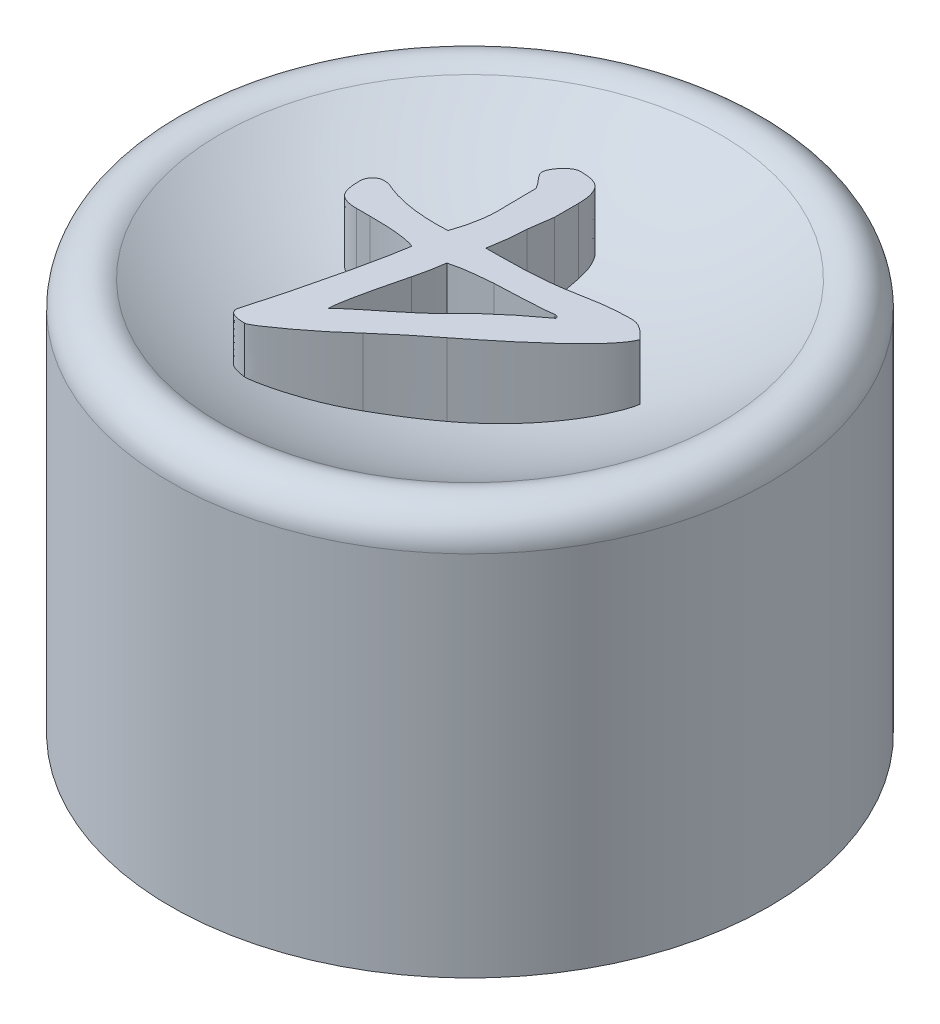
SolidWorks part; units mm, degrees
ref_plane "Front Plane" through (0, 0, 0) normal (0, 0, 1) x (1, 0, 0)
ref_plane "Top Plane" through (0, 0, 0) normal (0, 1, 0) x (1, 0, 0)
ref_plane "Right Plane" through (0, 0, 0) normal (1, 0, 0) x (0, 0, -1)
sketch "Sketch1" plane through (0, 0, 0) normal (0, 0, 1) x (1, 0, 0)
  line L0 (0, 0) -> (0, -66.4851) construction
  line L1 (55, 0) -> (-55, 0) construction
  line L2 (-1.5494, 0) -> (-1.5494, 3.048)
  line L3 (-1.5494, 3.048) -> (-0.762, 3.048)
  line L4 (-0.762, 3.048) -> (-0.762, 4.064)
  line L5 (-0.762, 4.064) -> (0, 4.064)
  line L6 (0, -55) -> (0, 55) construction
  line L7 (0, 4.064) -> (0, 5.08)
  line L8 (-4.7625, 5.842) -> (-4.7625, 0)
  line L9 (-4.7625, 0) -> (-3.4925, 0)
  line L10 (-3.4925, 0) -> (-3.4925, 4.064)
  line L11 (-3.4925, 4.064) -> (-2.0574, 4.064)
  line L12 (-2.0574, 4.064) -> (-2.0574, 0)
  line L13 (-2.0574, 0) -> (-1.5494, 0)
  line L14 (0, 5.08) -> (3.3062, 5.08) construction
  arc A0 (-4.7625, 5.842) -> (-3.976, 6.2669) centre (-4.2545, 5.842) cw
  arc A1 (-3.976, 6.2669) -> (0, 5.08) centre (0, 12.3333) ccw
  dimension "D4" = 1.524
  dimension "D5" = 6.35
  dimension "D9" = 0.508
  dimension "D1" = 9.525
  dimension "D2" = 3.0988
  dimension "D3" = 3.048
  dimension "D6" = 0.508
  dimension "D7" = 1.016
  dimension "D8" = 1.27
  dimension "D10" = 5.08
revolve "Revolve1" add sketch "Sketch1" angle 360 about L0
ref_plane "Plane1" through (0, 6.35, 0) normal (0, 1, 0) x (-1, 0, 0)
sketch "Sketch3" plane through (0, 6.35, 0) normal (0, 1, 0) x (-1, 0, 0)
  line L0 (-2.3812, -2.032) -> (2.3813, -2.032) construction
  line L1 (0, 0) -> (0, -7.9672) construction
  line L2 (0, 3.4925) -> (0, -3.4925) construction
  line L3 (3.4925, 0) -> (-3.4925, 0) construction
  text T0 "4" font "Segoe Print" height 4.7625
  dimension "D1" = 2.032
  dimension "D2" = 4.7625
extrude "Boss-Extrude1" add sketch "Sketch3" against normal up to surface (0.9361 mm away)
